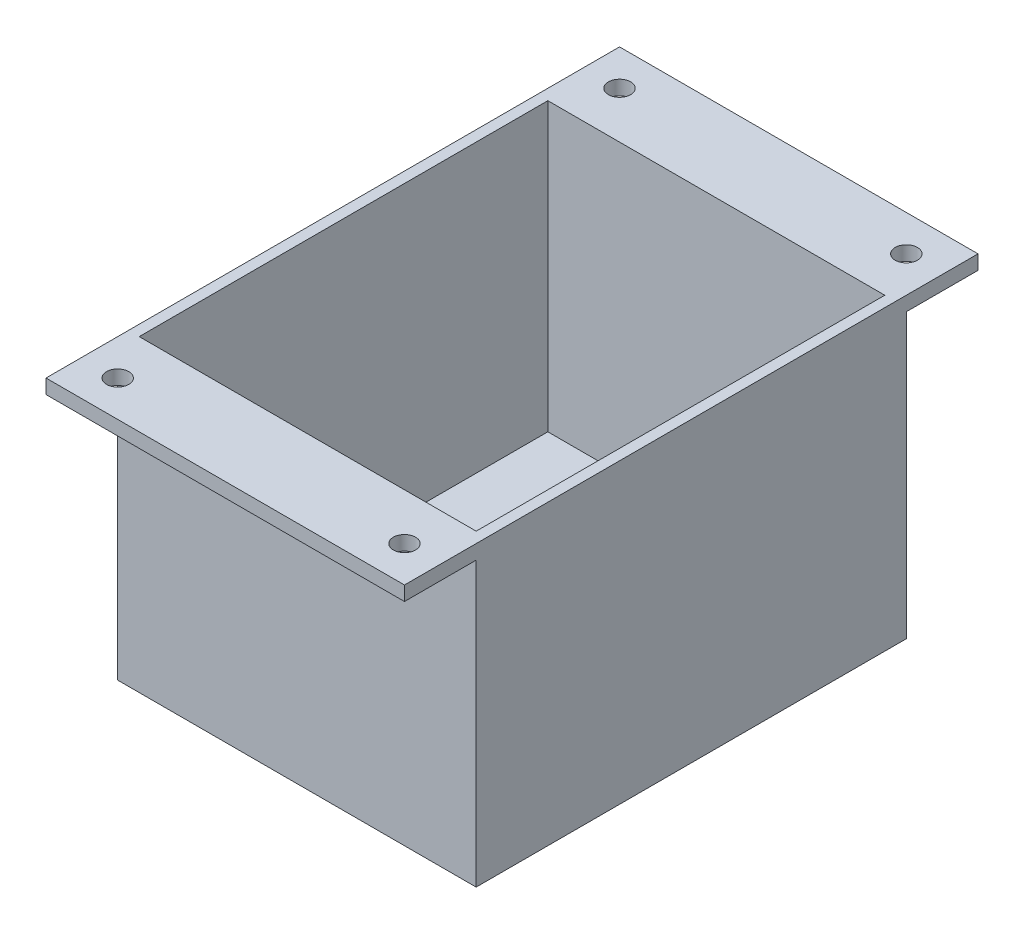
SolidWorks part; units mm, degrees
ref_plane "Płaszczyzna przednia" through (0, 0, 0) normal (0, 0, 1) x (1, 0, 0)
ref_plane "Płaszczyzna górna" through (0, 0, 0) normal (0, 1, 0) x (1, 0, 0)
ref_plane "Płaszczyzna prawa" through (0, 0, 0) normal (1, 0, 0) x (0, 0, -1)
sketch "Sketch1" plane through (0, 0, 0) normal (0, 1, 0) x (1, 0, 0)
  line L9 (-25, -40) -> (25, -40)
  line L16 (-25, -40) -> (-25, 40)
  line L21 (-25, 40) -> (25, 40)
  line L23 (25, -40) -> (25, 40)
  line L24 (-23.5, -28.5) -> (23.5, -28.5)
  line L25 (-23.5, -28.5) -> (-23.5, 28.5)
  line L26 (-25, -30) -> (25, -30)
  line L27 (-25, -30) -> (-25, 30)
  line L28 (-25, 30) -> (25, 30)
  line L29 (25, -30) -> (25, 30)
  line L30 (-23.5, 28.5) -> (23.5, 28.5)
  line L31 (23.5, -28.5) -> (23.5, 28.5)
  line L32 (-23.5, -28.5) -> (23.5, 28.5) construction
  line L33 (-23.5, 28.5) -> (23.5, -28.5) construction
  point P0 (0, 0)
  point P1 (0, 0)
  point P5 (0, 0)
  point P8 (0, 0)
  point P11 (0, 0)
  point P14 (0, 0)
  dimension "D1" = 50
  dimension "D2" = 80
  dimension "D3" = 50
  dimension "D4" = 60
  dimension "D5" = 47
  dimension "D6" = 57
extrude "Boss-Extrude6" add sketch "Sketch1" along normal blind 40 contours L28 L16 L26 L23 L31 L24 L25 L30
sketch "Sketch7" plane through (0, 0, 0) normal (0, -1, 0) x (1, 0, 0)
  line L1 (-25, 30) -> (25, 30)
  line L2 (-25, 30) -> (-25, -30)
  line L3 (-25, -30) -> (25, -30)
  line L4 (25, 30) -> (25, -30)
extrude "Boss-Extrude8" add sketch "Sketch7" along normal blind 1.5
sketch "Sketch8" plane through (25, 0, 0) normal (1, 0, 0) x (0, 0, -1)
  line L1 (-30, 40) -> (-40, 40)
  line L2 (-30, 40) -> (-30, 38)
  line L3 (-30, 38) -> (-40, 38)
  line L4 (-40, 40) -> (-40, 38)
  line L5 (30, 40) -> (40, 40)
  line L6 (30, 40) -> (30, 38)
  line L7 (30, 38) -> (40, 38)
  line L8 (40, 40) -> (40, 38)
  dimension "D1" = 10
  dimension "D2" = 2
  dimension "D3" = 10
  dimension "D4" = 2
extrude "Boss-Extrude9" add sketch "Sketch8" against normal blind 50
sketch "Sketch9" plane through (0, 40, 0) normal (0, 1, 0) x (1, 0, 0)
  circle A0 centre (-20, 35) radius 1.55
  circle A1 centre (20, 35) radius 1.55
  circle A2 centre (20, -35) radius 1.55
  circle A3 centre (-20, -35) radius 1.55
  point P0 (0, 0)
  dimension "D1" = 40
  dimension "D2" = 70
extrude "Cut-Extrude1" cut sketch "Sketch9" against normal blind 3
